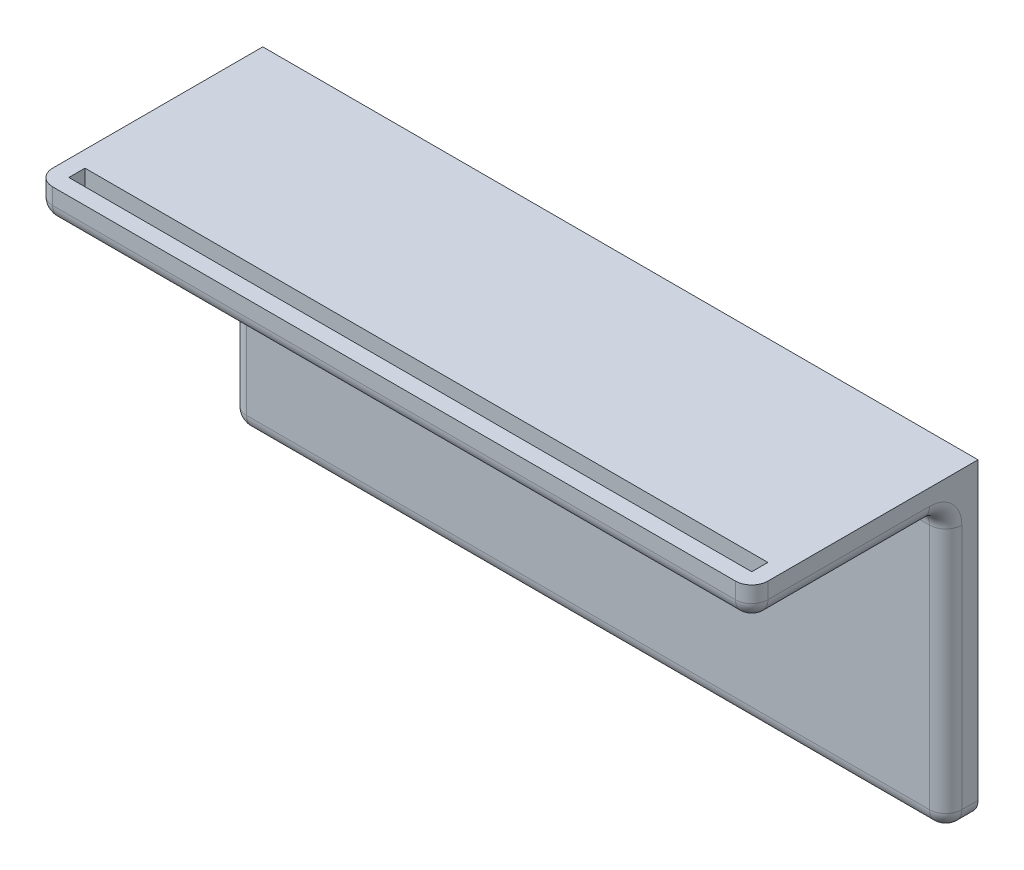
SolidWorks part; units mm, degrees
ref_plane "Front Plane" through (0, 0, 0) normal (1, 0, 0) x (0, 1, 0)
ref_plane "Top Plane" through (0, 0, 0) normal (0, 0, 1) x (0, 1, 0)
ref_plane "Right Plane" through (0, 0, 0) normal (0, 1, 0) x (-1, 0, 0)
sketch "Sketch1" plane through (0, 0, 0) normal (0, 0, 1) x (0, 1, 0)
  line L1 (-19.25, 44.25) -> (19.25, 44.25)
  line L2 (-19.25, 44.25) -> (-19.25, -44.25)
  line L3 (-19.25, -44.25) -> (19.25, -44.25)
  line L4 (19.25, 44.25) -> (19.25, -44.25)
  line L5 (-19.25, 44.25) -> (19.25, -44.25) construction
  line L6 (-19.25, -44.25) -> (19.25, 44.25) construction
  point P0 (0, 0)
  dimension "D1" = 38.5
  dimension "D2" = 88.5
extrude "Boss-Extrude1" add sketch "Sketch1" along normal blind 28
sketch "Sketch2" plane through (44.25, 0, 0) normal (1, 0, 0) x (0, 1, 0)
  line L0 (-19.25, 4) -> (15.25, 4)
  line L1 (-19.25, 28) -> (-19.25, 0) construction
  line L2 (15.25, 4) -> (15.25, 28)
  line L3 (-19.25, 28) -> (19.25, 28) construction
  line L4 (-19.25, 0) -> (19.25, 0) construction
  line L5 (19.25, 28) -> (19.25, 0) construction
  line L6 (-19.25, 4) -> (-19.25, 28)
  line L7 (-19.25, 28) -> (15.25, 28)
  dimension "D1" = 4
  dimension "D2" = 4
extrude "Cut-Extrude1" cut sketch "Sketch2" against normal blind 88.5
fillet "Fillet1" radius 2 1 edges at (0, 15.25, 4)
fillet "Fillet2" radius 2 1 edges at (0, 15.25, 28)
fillet "Fillet3" radius 2 1 edges at (0, -19.25, 4)
fillet "Fillet4" radius 2 7 edges at (44.25, 15.8358, 27.4142) (44.25, 15.25, 16) (44.25, 14.6642, 4.5858) (44.25, -2, 4) (44.25, -18.6642, 3.4142) (44.25, 18.25, 28) (44.25, -19.25, 1)
fillet "Fillet5" radius 2 7 edges at (-44.25, -18.6642, 3.4142) (-44.25, -2, 4) (-44.25, 14.6642, 4.5858) (-44.25, 15.25, 16) (-44.25, 15.8358, 27.4142) (-44.25, -19.25, 1) (-44.25, 18.25, 28)
sketch "Sketch3" plane through (0, 19.25, 0) normal (0, 1, 0) x (-1, 0, 0)
  line L0 (-42.25, 26) -> (42.25, 26)
  line L4 (42.25, 24) -> (-42.25, 24)
  line L7 (-42.25, 26) -> (-42.25, 24)
  line L9 (42.25, 26) -> (42.25, 24)
  line L10 (44.25, 26) -> (44.25, 0) construction
  dimension "D1" = 2
  dimension "D2" = 2
extrude "Cut-Extrude2" cut sketch "Sketch3" against normal blind 2
